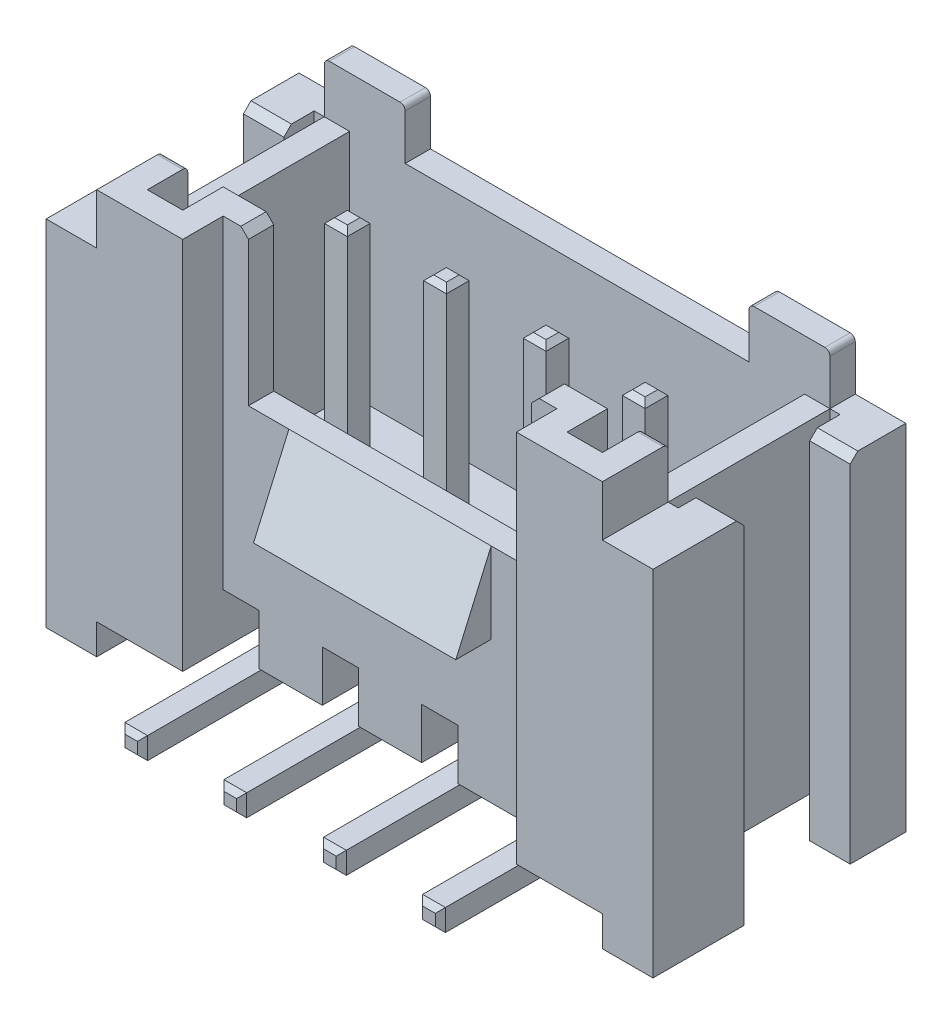
SolidWorks part; units mm, degrees
ref_plane "Plan de face" through (0, 0, 0) normal (0, 0, 1) x (1, 0, 0)
ref_plane "Plan de dessus" through (0, 0, 0) normal (0, 1, 0) x (1, 0, 0)
ref_plane "Plan de droite" through (0, 0, 0) normal (1, 0, 0) x (0, 0, -1)
sketch "Esquisse1" plane through (0, 0, 0) normal (0, 1, 0) x (1, 0, 0)
  line L1 (0, 0) -> (10, 0)
  line L2 (0, 0) -> (0, 5)
  line L3 (0, 5) -> (10, 5)
  line L4 (10, 0) -> (10, 5)
  dimension "D1" = 5
  dimension "D2" = 10
extrude "Boss.-Extru.1" add sketch "Esquisse1" along normal blind 7.4
sketch "Esquisse2" plane through (0, 7.4, 0) normal (0, 1, 0) x (1, 0, 0)
  line L0 (0, 0) -> (10, 0) construction
  line L1 (1.7, 0) -> (8.3, 0)
  line L2 (1.7, 0) -> (1.7, 0.8)
  line L3 (1.7, 0.8) -> (8.3, 0.8)
  line L4 (8.3, 0) -> (8.3, 0.8)
  line L5 (0, 5) -> (0, 0) construction
  line L6 (10, 0) -> (10, 5) construction
  dimension "D1" = 1.7
  dimension "D2" = 1.7
  dimension "D3" = 0.8
extrude "Enlèv. mat.-Extru.1" cut sketch "Esquisse2" against normal blind 8
sketch "Esquisse4" plane through (0, 7.4, 0) normal (0, 1, 0) x (1, 0, 0)
  line L16 (0.5, 0.5) -> (1.2, 0.5)
  line L17 (1.2, 0.5) -> (1.2, 1.3)
  line L18 (1.2, 1.3) -> (8.8, 1.3)
  line L19 (8.8, 1.3) -> (8.8, 0.5)
  line L20 (8.8, 0.5) -> (9.5, 0.5)
  line L21 (9.5, 0.5) -> (9.5, 4.5)
  line L22 (9.5, 4.5) -> (0.5, 4.5)
  line L23 (0.5, 4.5) -> (0.5, 0.5)
  line L24 (0.5, 0.5) -> (1.2, 0.5)
  line L25 (1.2, 0.5) -> (1.2, 1.3)
  line L26 (1.2, 1.3) -> (8.8, 1.3)
  line L27 (8.8, 1.3) -> (8.8, 0.5)
  line L28 (8.8, 0.5) -> (9.5, 0.5)
  line L29 (9.5, 0.5) -> (9.5, 4.5)
  line L30 (9.5, 4.5) -> (0.5, 4.5)
  line L31 (0.5, 4.5) -> (0.5, 0.5)
  dimension "D1" = 0.5
extrude "Enlèv. mat.-Extru.2" cut sketch "Esquisse4" against normal blind 5.5
sketch "Esquisse5" plane through (0, 7.4, 0) normal (0, 1, 0) x (1, 0, 0)
  line L0 (10, 5) -> (0, 5) construction
  line L1 (1.6, 5) -> (8.4, 5)
  line L2 (1.6, 5) -> (1.6, 4.5)
  line L3 (1.6, 4.5) -> (8.4, 4.5)
  line L4 (8.4, 5) -> (8.4, 4.5)
  line L5 (9.5, 4.5) -> (0.5, 4.5) construction
  line L6 (10, 0) -> (10, 5) construction
  line L7 (0, 5) -> (0, 0) construction
  line L8 (0.5, 4.5) -> (0.5, 0.5) construction
  line L9 (0, 4.5) -> (0.5, 4.5)
  line L10 (0, 4.5) -> (0, 1.3)
  line L11 (0, 1.3) -> (0.5, 1.3)
  line L12 (0.5, 4.5) -> (0.5, 1.3)
  line L13 (9.5, 0.5) -> (9.5, 4.5) construction
  line L14 (9.5, 4.5) -> (10, 4.5)
  line L15 (9.5, 4.5) -> (9.5, 1.3)
  line L16 (9.5, 1.3) -> (10, 1.3)
  line L17 (10, 4.5) -> (10, 1.3)
  line L18 (0, 0) -> (1.7, 0) construction
  line L19 (8.3, 0) -> (10, 0) construction
  dimension "D1" = 1.6
  dimension "D2" = 1.6
  dimension "D3" = 0.5
  dimension "D4" = 1.3
  dimension "D5" = 0.5
  dimension "D6" = 1.3
extrude "Enlèv. mat.-Extru.3" cut sketch "Esquisse5" against normal blind 1
sketch "Esquisse6" plane through (0, 7.4, 0) normal (0, 1, 0) x (1, 0, 0)
  line L0 (1.2, 1.3) -> (8.8, 1.3) construction
  line L1 (2.2, 1.3) -> (7.8, 1.3)
  line L2 (2.2, 1.3) -> (2.2, 0.8)
  line L3 (2.2, 0.8) -> (7.8, 0.8)
  line L4 (7.8, 1.3) -> (7.8, 0.8)
  line L5 (8.3, 0.8) -> (1.7, 0.8) construction
  line L6 (10, 0) -> (10, 1.3) construction
  line L7 (0, 5) -> (0, 4.5) construction
  dimension "D1" = 2.2
  dimension "D2" = 2.2
extrude "Enlèv. mat.-Extru.4" cut sketch "Esquisse6" against normal blind 3
sketch "Esquisse8" plane through (0, 0, 0) normal (0, -1, 0) x (1, 0, 0)
  line L0 (8.3, -0.8) -> (1.7, -0.8) construction
  line L1 (1.7, -0.8) -> (8.3, -0.8)
  line L2 (1.7, -0.8) -> (1.7, -5)
  line L3 (1.7, -5) -> (8.3, -5)
  line L4 (8.3, -0.8) -> (8.3, -5)
  line L5 (10, -5) -> (0, -5) construction
  line L6 (0, -5) -> (0, 0) construction
  line L7 (10, 0) -> (10, -5) construction
  dimension "D1" = 1.7
  dimension "D2" = 1.7
extrude "Enlèv. mat.-Extru.6" cut sketch "Esquisse8" against normal blind 1
sketch "Esquisse9" plane through (1.7, 0, 0) normal (1, 0, 0) x (0, 0, -1)
  line L0 (5, 1) -> (0.8, 1) construction
  line L1 (4.7, 1) -> (3.9, 0.2)
  line L2 (3.9, 0.2) -> (1.9, 0.2)
  line L3 (1.9, 0.2) -> (1.1, 1)
  line L4 (0, 0) -> (5, 0) construction
  line L5 (4.7, 1) -> (1.1, 1)
  dimension "D1" = 45
  dimension "D2" = 45
  dimension "D3" = 0.2
  dimension "D4" = 0.3
  dimension "D5" = 0.3
extrude "Boss.-Extru.2" add sketch "Esquisse9" along normal blind 6.8
ref_plane "Plan1" through (5, 0, 0) normal (1, 0, 0) x (0, 0, -1)
sketch "Esquisse11" plane through (5, 0, 0) normal (1, 0, 0) x (0, 0, -1)
  line L0 (0.8, 4.4) -> (0.1, 2.8)
  line L1 (0.1, 2.8) -> (0.8, 2.8)
  line L2 (0.8, 1) -> (0.8, 7.4) construction
  line L3 (0.8, 2.8) -> (0.8, 4.4)
  dimension "D1" = 1.6
  dimension "D2" = 0.7
extrude "Boss.-Extru.3" add sketch "Esquisse11" along normal blind 2 and the other way blind 2
ref_plane "Plan2" through (0, 1, 0) normal (0, 1, 0) x (1, 0, 0)
sketch "Esquisse17" plane through (0, 1, 0) normal (0, 1, 0) x (1, 0, 0)
  line L0 (3.035, 0.8) -> (3.035, 5) construction
  line L1 (5, 0.8) -> (5, 5) construction
  line L2 (6.965, 0.8) -> (6.965, 5) construction
  line L4 (1.7, 0.8) -> (1.7, 5) construction
  line L8 (2.41, 0.8) -> (3.66, 0.8)
  line L9 (3.66, 0.8) -> (3.66, 5)
  line L10 (3.66, 5) -> (2.41, 5)
  line L11 (2.41, 5) -> (2.41, 0.8)
  line L16 (4.375, 0.8) -> (5.625, 0.8)
  line L17 (5.625, 0.8) -> (5.625, 5)
  line L18 (5.625, 5) -> (4.375, 5)
  line L19 (4.375, 5) -> (4.375, 0.8)
  line L24 (6.34, 0.8) -> (7.59, 0.8)
  line L25 (7.59, 0.8) -> (7.59, 5)
  line L26 (7.59, 5) -> (6.34, 5)
  line L27 (6.34, 5) -> (6.34, 0.8)
  dimension "D1" = 1.25
  dimension "D2" = 1.25
  dimension "D3" = 1.25
  dimension "D4" = 3.3
  dimension "D5" = 1.34
  dimension "D6" = 1.34
extrude "Boss.-Extru.8" add sketch "Esquisse17" against normal blind 1
chamfer "Chanfrein1" distance 0.15 angle 45 2 edges at (2.2, 7.4, -1.05) (7.8, 7.4, -1.05)
sketch "Esquisse13" plane through (0, 0.2, 0) normal (0, -1, 0) x (1, 0, 0)
  line L0 (5, -0.8) -> (5, -5) construction
  line L1 (1.83, -2.675) -> (2.28, -2.675)
  line L2 (1.83, -2.675) -> (1.83, -3.125)
  line L3 (1.83, -3.125) -> (2.28, -3.125)
  line L4 (2.28, -2.675) -> (2.28, -3.125)
  line L5 (4.24, -3.125) -> (3.79, -3.125)
  line L6 (3.79, -2.675) -> (3.79, -3.125)
  line L7 (4.24, -2.675) -> (4.24, -3.125)
  line L8 (4.24, -2.675) -> (3.79, -2.675)
  line L9 (2.055, -2.675) -> (2.055, -3.125) construction
  line L10 (1.7, -1.9) -> (1.7, -3.9) construction
  line L11 (2.41, -0.8) -> (3.66, -0.8) construction
  line L14 (1.83, -2.9) -> (2.28, -2.9) construction
  line L15 (2.41, -1.9) -> (1.7, -1.9) construction
  line L16 (3.035, -0.8) -> (3.035, -5) construction
  line L19 (5.76, -3.125) -> (6.21, -3.125)
  line L20 (5.76, -2.675) -> (5.76, -3.125)
  line L21 (5.76, -2.675) -> (6.21, -2.675)
  line L22 (6.21, -2.675) -> (6.21, -3.125)
  line L23 (7.72, -2.675) -> (7.72, -3.125)
  line L24 (8.17, -3.125) -> (7.72, -3.125)
  line L25 (8.17, -2.675) -> (8.17, -3.125)
  line L26 (8.17, -2.675) -> (7.72, -2.675)
  point P14 (3.035, -0.8)
  dimension "D1" = 0.355
  dimension "D2" = 0.45
  dimension "D3" = 0.45
  dimension "D4" = 1
  dimension "D5" = 0
extrude "Boss.-Extru.5" add sketch "Esquisse13" along normal blind 0.8 and the other way blind 6.3
fillet "Congé2" radius 0.1 6 edges at (0.25, 7.4, -1.3) (0, 7.4, -4.75) (1.6, 7.4, -4.75) (8.4, 7.4, -4.75) (10, 7.4, -4.75) (9.75, 7.4, -1.3)
chamfer "Chanfrein2" distance 0.1 angle 45 16 edges at (7.945, 6.5, -2.675) (8.17, 6.5, -2.9) (7.72, 6.5, -2.9) (7.945, 6.5, -3.125) (5.985, 6.5, -2.675) (6.21, 6.5, -2.9) (5.985, 6.5, -3.125) (5.76, 6.5, -2.9) (4.015, 6.5, -2.675) (4.24, 6.5, -2.9) (4.015, 6.5, -3.125) (3.79, 6.5, -2.9) (1.83, 6.5, -2.9) (2.055, 6.5, -3.125) (2.28, 6.5, -2.9) (2.055, 6.5, -2.675)
sketch "Esquisse14" plane through (0, 0, -3.125) normal (0, 0, -1) x (-1, 0, 0)
  line L0 (-7.72, 0.2) -> (-7.72, -0.6) construction
  line L1 (-8.17, -0.6) -> (-7.72, -0.6)
  line L2 (-8.17, -0.6) -> (-8.17, -0.17)
  line L3 (-8.17, -0.17) -> (-7.72, -0.17)
  line L4 (-7.72, -0.6) -> (-7.72, -0.17)
  line L5 (-6.965, 0) -> (-6.965, 1.119) construction
  line L6 (-7.59, 0) -> (-6.34, 0) construction
  line L7 (-5, 0) -> (-5, 1.119) construction
  line L9 (-5.76, -0.6) -> (-6.21, -0.6)
  line L10 (-6.21, -0.6) -> (-6.21, -0.17)
  line L11 (-5.76, -0.6) -> (-5.76, -0.17)
  line L12 (-5.76, -0.17) -> (-6.21, -0.17)
  line L13 (-4.24, -0.6) -> (-3.79, -0.6)
  line L14 (-4.24, -0.6) -> (-4.24, -0.17)
  line L15 (-4.24, -0.17) -> (-3.79, -0.17)
  line L16 (-3.79, -0.6) -> (-3.79, -0.17)
  line L17 (-1.83, -0.6) -> (-2.28, -0.6)
  line L18 (-2.28, -0.6) -> (-2.28, -0.17)
  line L19 (-1.83, -0.6) -> (-1.83, -0.17)
  line L20 (-1.83, -0.17) -> (-2.28, -0.17)
  point P9 (-6.965, 0)
  dimension "D1" = 0.43
  dimension "D2" = 0
extrude "Boss.-Extru.6" add sketch "Esquisse14" against normal blind 4.5
chamfer "Chanfrein3" distance 0.1 angle 45 16 edges at (2.055, -0.6, 1.375) (2.28, -0.385, 1.375) (2.055, -0.17, 1.375) (1.83, -0.385, 1.375) (4.015, -0.17, 1.375) (3.79, -0.385, 1.375) (4.015, -0.6, 1.375) (4.24, -0.385, 1.375) (5.985, -0.6, 1.375) (6.21, -0.385, 1.375) (5.985, -0.17, 1.375) (5.76, -0.385, 1.375) (7.945, -0.17, 1.375) (7.72, -0.385, 1.375) (7.945, -0.6, 1.375) (8.17, -0.385, 1.375)
sketch "Esquisse16" plane through (0, 6.4, 0) normal (0, 1, 0) x (1, 0, 0)
  line L0 (0, 5) -> (-1, 5) construction
  line L1 (-1, 5) -> (-1, 0) construction
  line L2 (-1, 0) -> (0, 0) construction
  line L3 (0, 1.2) -> (0, 0) construction
  line L5 (0, 4.5) -> (-0.2, 4.5)
  line L6 (0, 4.5) -> (0, 5)
  line L7 (0, 5) -> (-0.2, 5)
  line L8 (0, 0) -> (-1, 0)
  line L9 (-1, 5) -> (-0.2, 5)
  line L10 (-1, 5) -> (-1, 3.9)
  line L11 (-1, 3.9) -> (-0.2, 3.9)
  line L12 (-0.2, 4.5) -> (-0.2, 3.9)
  line L13 (0, 0) -> (0, 1.3)
  line L14 (0, 1.3) -> (-0.2, 1.3)
  line L15 (-1, 0) -> (-1, 1.3)
  line L16 (0, 1.3) -> (0.5, 1.3) construction
  line L17 (-1, 1.3) -> (-1, 1.8)
  line L18 (-1, 1.8) -> (-0.2, 1.8)
  line L19 (-0.2, 1.3) -> (-0.2, 1.8)
  line L20 (5, 5) -> (5, 0.8) construction
  line L21 (8.4, 5) -> (1.6, 5) construction
  line L22 (3, 0.8) -> (7, 0.8) construction
  line L23 (10.2, 4.5) -> (10.2, 3.9)
  line L24 (11, 1.3) -> (11, 1.8)
  line L25 (11, 0) -> (11, 1.3)
  line L26 (10, 0) -> (11, 0)
  line L27 (10, 0) -> (10, 1.3)
  line L28 (10, 1.3) -> (10.2, 1.3)
  line L29 (10.2, 1.3) -> (10.2, 1.8)
  line L30 (11, 1.8) -> (10.2, 1.8)
  line L31 (10, 4.5) -> (10.2, 4.5)
  line L32 (10, 4.5) -> (10, 5)
  line L33 (10, 5) -> (10.2, 5)
  line L34 (11, 5) -> (10.2, 5)
  line L35 (11, 5) -> (11, 3.9)
  line L36 (11, 3.9) -> (10.2, 3.9)
  line L37 (0, 5) -> (0, 4.5)
  line L38 (0, 1.3) -> (0, 0)
  line L39 (10, 1.3) -> (10, 0)
  line L40 (10, 4.5) -> (10, 5)
  dimension "D1" = 1
  dimension "D2" = 0.8
  dimension "D3" = 1.1
  dimension "D4" = 0.8
  dimension "D5" = 1.8
  dimension "D6" = 0
extrude "Boss.-Extru.7" add sketch "Esquisse16" against normal blind 7 contours L14 L19 L18 L17 L15 L8 L13 | L12 L5 L6 L7 L9 L10 L11 | L36 L35 L34 L33 L32 L31 L23 | L24 L30 L29 L28 L27 L26 L25
chamfer "Chanfrein4" distance 0.15 angle 45 4 edges at (10.6, 6.4, -3.9) (10.6, 6.4, -1.8) (-0.6, 6.4, -1.8) (-0.6, 6.4, -3.9)
fillet "Congé3" radius 0.1 8 edges at (2.055, -0.17, -2.675) (4.015, -0.17, -2.675) (5.985, -0.17, -2.675) (7.945, -0.17, -2.675) (2.055, -0.6, -3.125) (4.015, -0.6, -3.125) (5.985, -0.6, -3.125) (7.945, -0.6, -3.125)
